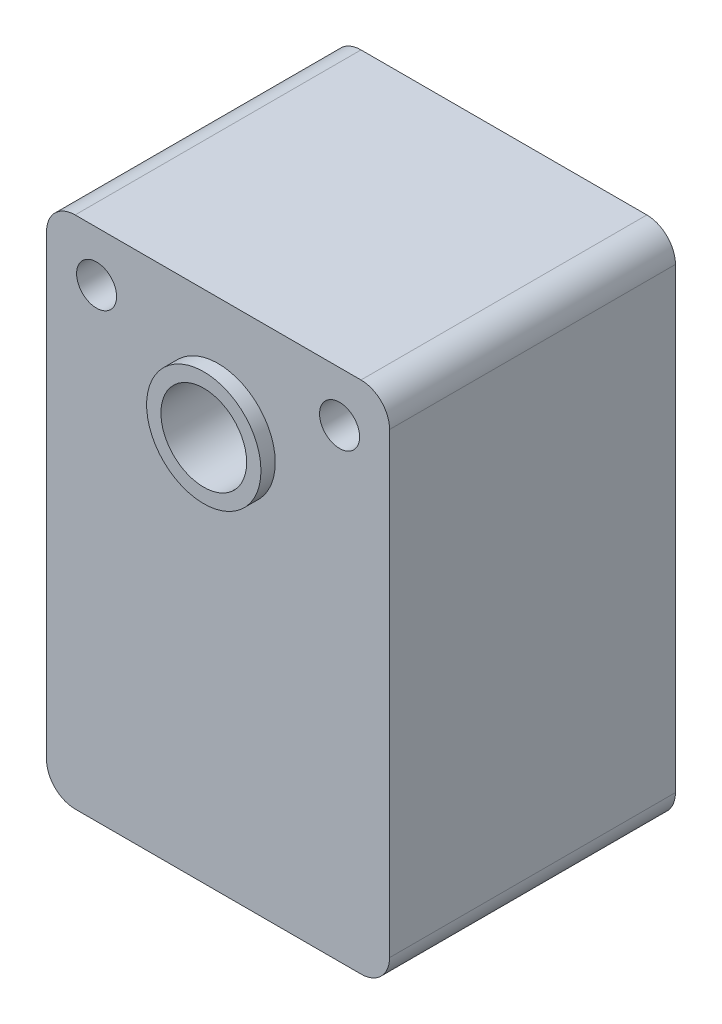
SolidWorks part; units mm, degrees
ref_plane "前视基准面" through (0, 0, 0) normal (0, 0, 1) x (1, 0, 0)
ref_plane "上视基准面" through (0, 0, 0) normal (0, 1, 0) x (1, 0, 0)
ref_plane "右视基准面" through (0, 0, 0) normal (1, 0, 0) x (0, 0, -1)
sketch "草图1" plane through (0, 0, 0) normal (0, 0, 1) x (1, 0, 0)
  line L0 (0, 9) -> (0, 5) construction
  line L1 (6, -9) -> (-6, -9)
  line L2 (6, -9) -> (6, 9)
  line L3 (6, 9) -> (-6, 9)
  line L4 (-6, -9) -> (-6, 9)
  line L5 (6, -9) -> (-6, 9) construction
  line L6 (6, 9) -> (-6, -9) construction
  circle A0 centre (0, 5) radius 1.5
  circle A1 centre (-4.25, 7.25) radius 0.7
  circle A2 centre (4.25, 7.25) radius 0.7
  point P0 (0, 0)
  dimension "D1" = 12
  dimension "D3" = 3
  dimension "D5" = 1.4
  dimension "D2" = 18
  dimension "D4" = 4
  dimension "D6" = 1.75
  dimension "D7" = 8.5
extrude "凸台-拉伸1" add sketch "草图1" along normal blind 10
sketch "草图2" plane through (0, 0, 10) normal (0, 0, 1) x (1, 0, 0)
  circle A0 centre (0, 5) radius 1.5
  circle A1 centre (0, 5) radius 2
extrude "凸台-拉伸2" add sketch "草图2" along normal blind 0.5
fillet "圆角1" radius 1 4 edges at (-6, -9, 5) (6, -9, 5) (6, 9, 5) (-6, 9, 5)
